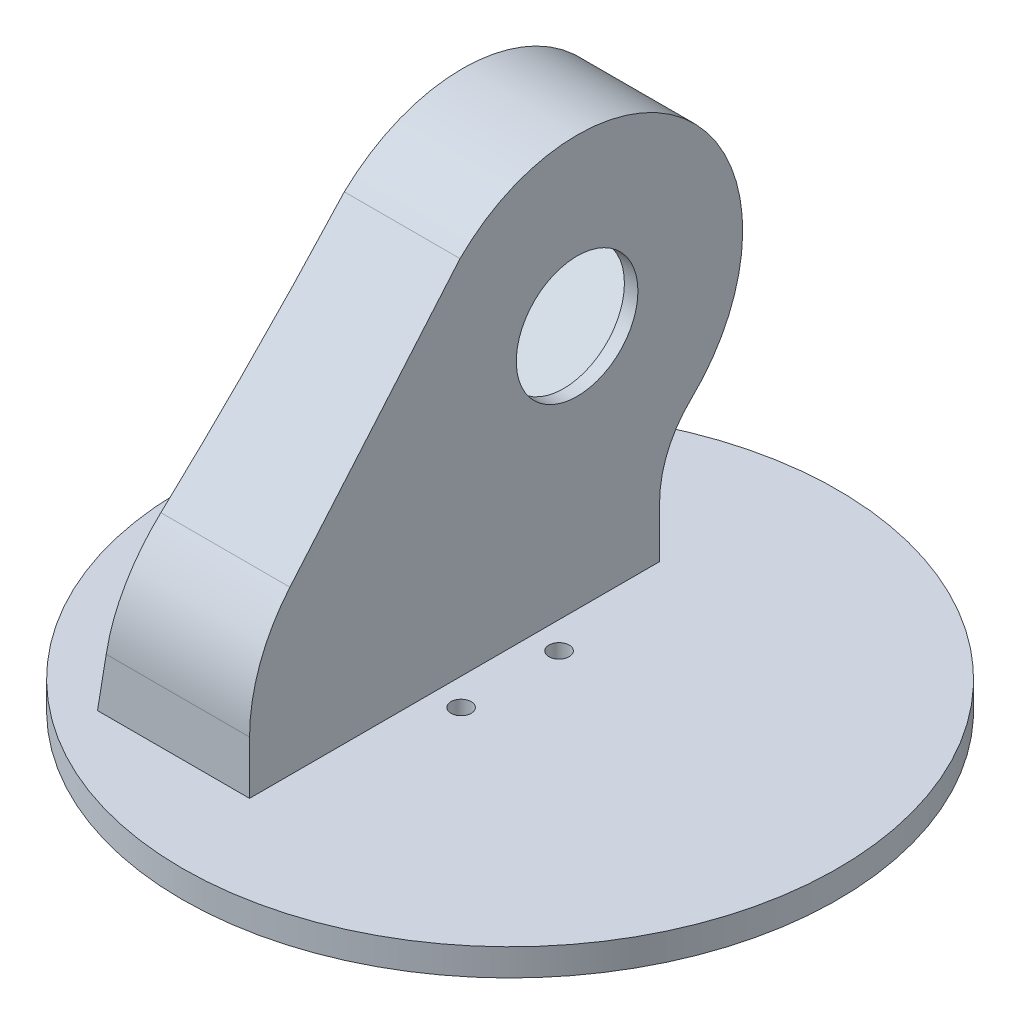
SolidWorks part; units mm, degrees
ref_plane "Front Plane" through (0, 0, 0) normal (0, 0, 1) x (1, 0, 0)
ref_plane "Top Plane" through (0, 0, 0) normal (0, 1, 0) x (1, 0, 0)
ref_plane "Right Plane" through (0, 0, 0) normal (1, 0, 0) x (0, 0, -1)
sketch "Sketch2" plane through (0, 0, 0) normal (0, 1, 0) x (1, 0, 0)
  circle A0 centre (0, 0) radius 48.5
  dimension "D1" = 97
extrude "Boss-Extrude1" add sketch "Sketch2" along normal blind 4
sketch "Sketch4" plane through (0, 0, 0) normal (0, -1, 0) x (1, 0, 0)
  circle A0 centre (0, 7.25) radius 1.5
  circle A1 centre (0, -7.25) radius 1.5
  dimension "D1" = 3
  dimension "D2" = 3
  dimension "D3" = 14.5
  dimension "D4" = 7.25
extrude "Cut-Extrude2" cut sketch "Sketch4" against normal through all
sketch "Sketch5" plane through (0, 0, 0) normal (0, -1, 0) x (1, 0, 0)
  circle A0 centre (0, 0) radius 3.75
  dimension "D1" = 7.5
extrude "Cut-Extrude3" cut sketch "Sketch5" against normal blind 1.5
ref_plane "Plane1" through (-4, 0, 0) normal (1, 0, 0) x (0, 0, -1)
sketch "Sketch7" plane through (-4, 0, 0) normal (1, 0, 0) x (0, 0, -1)
  line L0 (23.1299, 11.6445) -> (23.1299, 4)
  line L5 (48.5, 4) -> (-48.5, 4) construction
  line L6 (-27.2273, 29.5362) -> (-1.2843, 55.4793)
  line L7 (-43.5609, 4) -> (23.1299, 4)
  line L11 (-34.5496, 4) -> (-34.5496, 11.8586)
  arc A4 (28.7298, 24.692) -> (-1.2843, 55.4793) centre (13.9185, 40.2765) ccw
  arc A5 (28.7298, 24.692) -> (23.1299, 11.6445) centre (41.1299, 11.6445) ccw
  arc A6 (-27.2273, 29.5362) -> (-34.5496, 11.8586) centre (-9.5496, 11.8586) ccw
  dimension "D1" = 25
  dimension "D4" = 43
  dimension "D3" = 18
  dimension "D5" = 45
extrude "Boss-Extrude2" add sketch "Sketch7" against normal blind 14
ref_plane "Plane2" through (-6, 0, 0) normal (1, 0, 0) x (0, 0, -1)
sketch "Sketch8" plane through (-6, 0, 0) normal (1, 0, 0) x (0, 0, -1)
  line L0 (-27.2273, 29.5362) -> (-1.2843, 55.4793) construction
  line L1 (-15.2496, 25.9576) -> (13.7417, 54.9489)
  line L2 (-15.2496, 25.9576) -> (-0.4004, 11.1083)
  line L3 (-0.4004, 11.1083) -> (28.591, 40.0997)
  line L4 (13.7417, 54.9489) -> (28.591, 40.0997)
  line L5 (-15.2496, 25.9576) -> (28.591, 40.0997) construction
  line L6 (-0.4004, 11.1083) -> (13.7417, 54.9489) construction
  point P0 (6.6707, 33.0286)
  point P11 (13.9185, 40.2765)
  dimension "D1" = 41
  dimension "D2" = 21
  dimension "D3" = 90
  dimension "D4" = 20.5
  dimension "D5" = 90
  dimension "D6" = 10.25
  dimension "D7" = 10.5
extrude "Cut-Extrude5" cut sketch "Sketch8" against normal up to next
sketch "Sketch9" plane through (-18, 0, 0) normal (-1, 0, 0) x (0, 0, 1)
  line L0 (-13.7417, 54.9489) -> (-28.591, 40.0997) construction
  line L3 (-21.1664, 47.5243) -> (-22.536, 48.894) construction
  circle A0 centre (-20.1057, 53.5347) radius 1.3
  circle A1 centre (-27.1768, 46.4637) radius 1.3
  circle A2 centre (6.7644, 12.5225) radius 1.3
  circle A3 centre (13.8354, 19.5936) radius 1.3
  dimension "D1" = 2.6
  dimension "D5" = 5
  dimension "D6" = 90
  dimension "D2" = 3.5
  dimension "D3" = 2
  dimension "D4" = 2
extrude "Cut-Extrude6" cut sketch "Sketch9" against normal blind 7.5
sketch "Sketch11" plane through (-4, 0, 0) normal (1, 0, 0) x (0, 0, -1)
  circle A0 centre (13.9185, 40.2765) radius 9
  dimension "D1" = 18
extrude "Cut-Extrude9" cut sketch "Sketch11" against normal up to next
sketch "Sketch17" plane through (-18, 0, 0) normal (-1, 0, 0) x (0, 0, 1)
  line L0 (29.3486, 31.6576) -> (3.4056, 57.6006)
  line L1 (-26.1299, 11.6445) -> (-26.1299, 1)
  line L2 (-26.1299, 1) -> (37.5496, 1)
  line L3 (37.5496, 1) -> (37.5496, 11.8586)
  line L4 (27.2273, 29.5362) -> (1.2843, 55.4793)
  line L5 (-23.1299, 11.6445) -> (-23.1299, 4)
  line L6 (-23.1299, 4) -> (34.5496, 4)
  line L7 (34.5496, 4) -> (34.5496, 11.8586)
  line L9 (-23.1299, 11.6445) -> (-23.1299, 4)
  line L10 (-23.1299, 4) -> (34.5496, 4)
  line L11 (34.5496, 4) -> (34.5496, 11.8586)
  line L12 (-26.1299, 4) -> (37.5496, 4)
  line L13 (48.5, 4) -> (-48.5, 4) construction
  line L14 (3.4056, 57.6006) -> (28.5745, 28.0776)
  line L15 (1.2843, 55.4793) -> (26.295, 26.1272)
  line L16 (31.5496, 11.8586) -> (31.5496, 4)
  line L18 (27.2273, 29.5362) -> (1.2843, 55.4793) construction
  arc A0 (3.4056, 57.6006) -> (-30.7965, 22.5174) centre (-13.9185, 40.2765) ccw
  arc A1 (-26.1299, 11.6445) -> (-30.7965, 22.5174) centre (-41.1299, 11.6445) ccw
  arc A2 (37.5496, 11.8586) -> (29.3486, 31.6576) centre (9.5496, 11.8586) ccw
  arc A3 (1.2843, 55.4793) -> (-28.7298, 24.692) centre (-13.9185, 40.2765) ccw
  arc A4 (-23.1299, 11.6445) -> (-28.7298, 24.692) centre (-41.1299, 11.6445) ccw
  arc A5 (34.5496, 11.8586) -> (27.2273, 29.5362) centre (9.5496, 11.8586) ccw
  arc A6 (1.2843, 55.4793) -> (-28.7298, 24.692) centre (-13.9185, 40.2765) ccw
  arc A7 (-23.1299, 11.6445) -> (-28.7298, 24.692) centre (-41.1299, 11.6445) ccw
  arc A8 (34.5496, 11.8586) -> (27.2273, 29.5362) centre (9.5496, 11.8586) ccw
  arc A9 (31.5496, 11.8586) -> (25.106, 27.4149) centre (9.5496, 11.8586) ccw
  line M16 (27.2273, 29.5362) -> (1.2843, 55.4793)
  arc M17 (1.2843, 55.4793) -> (-28.7298, 24.692) centre (-13.9185, 40.2765) ccw
  arc M18 (-28.7298, 24.692) -> (-23.1299, 11.6445) centre (-41.1299, 11.6445) cw
  line M19 (-23.1299, 11.6445) -> (-23.1299, 4)
  line M21 (34.5496, 4) -> (34.5496, 11.8586)
  arc M22 (34.5496, 11.8586) -> (27.2273, 29.5362) centre (9.5496, 11.8586) ccw
  dimension "D1" = 0
  dimension "D2" = 3
  dimension "D3" = 3
extrude "Boss-Extrude7" add sketch "Sketch17" along normal blind 9 and the other way up to surface contours A9 L16 L12 L15 M21 M22 M16 | A1 L1 L12 L14 A0 M19 M18 M17 M16 M22 other way up to face at (-4, 40.2765, -22.9185)
sketch "Sketch25" plane through (-18, 0, 0) normal (-1, 0, 0) x (0, 0, 1)
  line L0 (-23.1299, 11.6445) -> (-23.1299, 4)
  line L1 (48.5, 4) -> (-48.5, 4) construction
  line L2 (-23.1299, 11.6445) -> (-23.1299, 4) construction
  line L3 (1.2843, 55.4793) -> (26.295, 26.1272) construction
  line L4 (31.5496, 4) -> (-23.1299, 4) construction
  line L5 (31.5496, 11.8586) -> (31.5496, 4) construction
  line L6 (31.5496, 4) -> (-23.1299, 4)
  line L7 (31.5496, 11.8586) -> (31.5496, 4)
  line L8 (1.2843, 55.4793) -> (26.295, 26.1272)
  arc A0 (-23.1299, 11.6445) -> (-28.7298, 24.692) centre (-41.1299, 11.6445) ccw construction
  arc A1 (1.2843, 55.4793) -> (-28.7298, 24.692) centre (-13.9185, 40.2765) ccw construction
  arc A2 (-23.1299, 11.6445) -> (-28.7298, 24.692) centre (-41.1299, 11.6445) ccw
  arc A3 (31.5496, 11.8586) -> (26.295, 26.1272) centre (9.5496, 11.8586) ccw construction
  arc A4 (31.5496, 11.8586) -> (26.295, 26.1272) centre (9.5496, 11.8586) ccw
  spline S0 degree 3 poles (-28.7298, 24.692) (-21.9549, 18.2532) (-19.0941, 12.798) (-15.1299, 4) knots 0 0 0 0 1 1 1 1
  spline S1 degree 2 poles (11.7516, 43.195) (26.5513, 25.8264) (25.5496, 4) knots 0 0 0 1 1 1
  dimension "D2" = 8
  dimension "D1" = 6
extrude "Boss-Extrude10" add sketch "Sketch25" along normal up to surface (9 mm away) contours S0 L6 L0 A2 | A4 S1 A2 S0 L8 up to face at (-27, 22.2911, 0.3951)
sketch "Sketch26" plane through (0, 0, 0) normal (0, 0, 1) x (1, 0, 0)
  line L0 (-4, 64.7765) -> (-27, 64.7765) construction
  line L1 (-27, 4) -> (-4, 4) construction
  line L2 (-27, 4) -> (-27, 11.8586) construction
  line L3 (-26, 64.7765) -> (-27, 64.7765)
  line L4 (-27, 64.7765) -> (-27, 4)
  line L5 (-27, 4) -> (-23, 4)
  spline S0 degree 2 poles (-26, 64.7765) (-24.7724, 34.3751) (-23, 4) knots 0 0 0 1 1 1
  dimension "D1" = 1
  dimension "D2" = 4
  dimension "D3" = 2
extrude "Cut-Extrude15" [suppressed] cut sketch "Sketch26" against normal through all both and the other way through all contours L4 L5 S0 L3
sketch "Sketch29" plane through (0, 0, 0) normal (0, 0, 1) x (1, 0, 0)
  line L0 (-4, 64.7765) -> (-27, 64.7765) construction
  line L1 (-27, 4) -> (-4, 4) construction
  line L2 (-21, 64.7765) -> (-27, 64.7765)
  line L3 (-27, 64.7765) -> (-27, 4)
  line L4 (-27, 4) -> (-26.5, 4)
  line L5 (48.5, 4) -> (-48.5, 4) construction
  spline S0 degree 2 poles (-21, 64.7765) (-21.2205, 34.1409) (-26.5, 4) knots 0 0 0 1 1 1
  dimension "D1" = 6
  dimension "D2" = 4
  dimension "D3" = 0.5
  dimension "D4" = 25
extrude "Cut-Extrude17" cut sketch "Sketch29" against normal through all both and the other way through all
